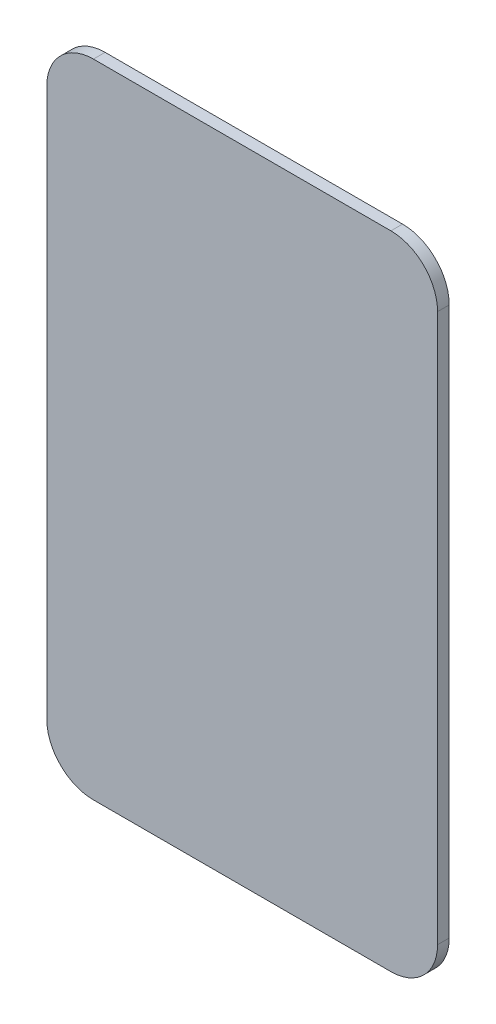
SolidWorks part; units mm, degrees
material "Glass"
ref_plane "Front Plane" through (0, 0, 0) normal (0, 0, 1) x (1, 0, 0)
ref_plane "Top Plane" through (0, 0, 0) normal (0, 1, 0) x (1, 0, 0)
ref_plane "Right Plane" through (0, 0, 0) normal (1, 0, 0) x (0, 0, -1)
sketch "Sketch2" plane through (0, 0, 0) normal (0, 0, 1) x (1, 0, 0)
  line L0 (63.5, 165.1) -> (63.5, 1358.9)
  line L5 (165.1, 1460.5) -> (812.8, 1460.5)
  line L6 (914.4, 165.1) -> (914.4, 1358.9)
  line L7 (165.1, 63.5) -> (812.8, 63.5)
  arc A0 (812.8, 1460.5) -> (914.4, 1358.9) centre (812.8, 1358.9) cw
  arc A1 (914.4, 165.1) -> (812.8, 63.5) centre (812.8, 165.1) cw
  arc A2 (63.5, 165.1) -> (165.1, 63.5) centre (165.1, 165.1) ccw
  arc A3 (63.5, 1358.9) -> (165.1, 1460.5) centre (165.1, 1358.9) cw
  dimension "D1" = 101.6
extrude "Boss-Extrude1" add sketch "Sketch2" along normal blind 25.4
